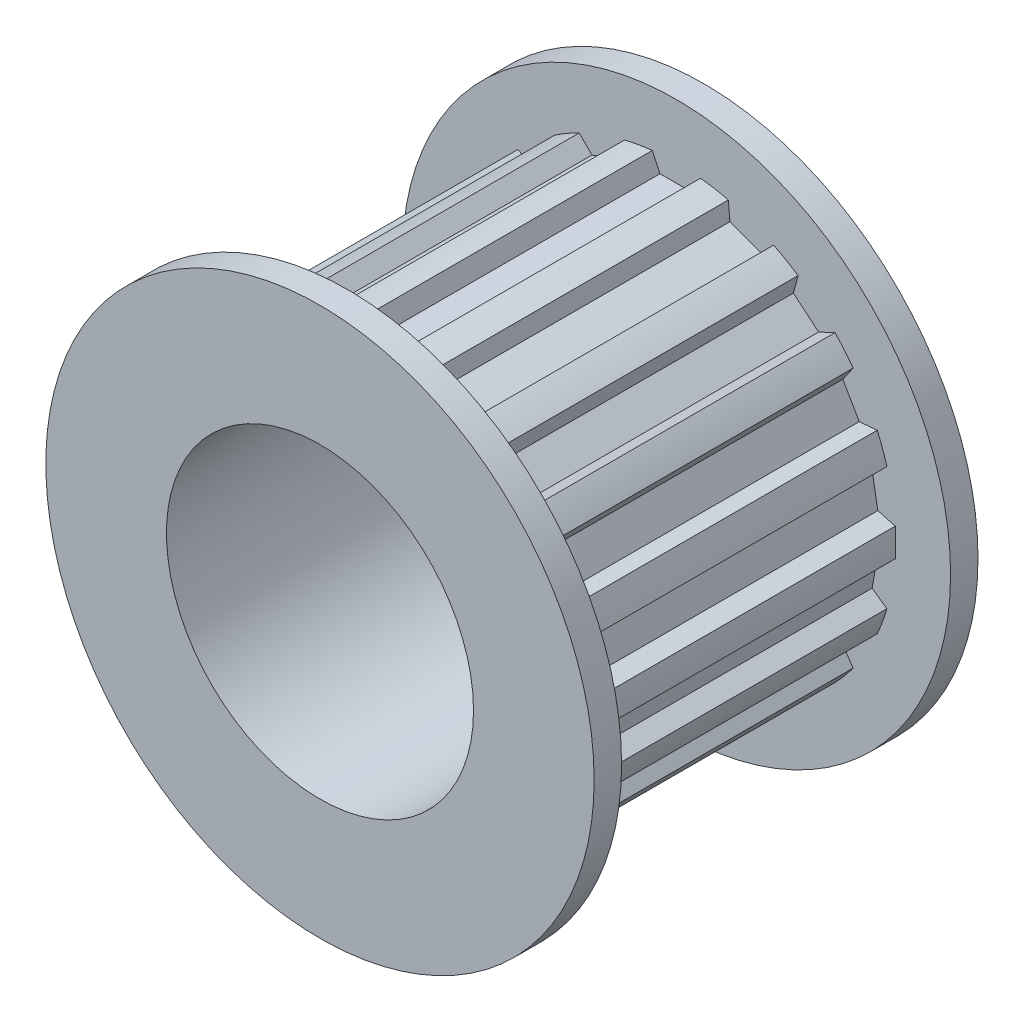
SolidWorks part; units mm, degrees
ref_plane "Plan de face" through (0, 0, 0) normal (0, 0, 1) x (1, 0, 0)
ref_plane "Plan de dessus" through (0, 0, 0) normal (0, 1, 0) x (1, 0, 0)
ref_plane "Plan de droite" through (0, 0, 0) normal (1, 0, 0) x (0, 0, -1)
sketch "Esquisse1" plane through (0, 0, 0) normal (0, 0, 1) x (1, 0, 0)
  circle A0 centre (0, 0) radius 8
  circle A1 centre (0, 0) radius 5.6
extrude "Extrusion1" add sketch "Esquisse1" along normal blind 12
sketch "Esquisse2" plane through (0, 0, 12) normal (0, 0, 1) x (1, 0, 0)
  line L0 (0, 0) -> (0, 16.2125) construction
  line L1 (-0.6, 7.3535) -> (0.6, 7.3535)
  line L2 (0.6, 7.3535) -> (1.0023, 8.2162)
  line L3 (1.0023, 8.2162) -> (-1.0023, 8.2162)
  line L4 (-1.0023, 8.2162) -> (-0.6, 7.3535)
  dimension "D1" = 25
  dimension "D2" = 50
  dimension "D3" = 0.6
  dimension "D4" = 0.6
extrude "Extrusion2" cut sketch "Esquisse2" against normal through all
pattern_circular "Répétition circulaire1" count 18 over 360 about axis through (0, 0, 0) along (0, 0, 1) of "Extrusion2"
sketch "Esquisse3" plane through (0, 0, 12) normal (0, 0, 1) x (1, 0, 0)
  circle A0 centre (0, 0) radius 10
  circle A1 centre (0, 0) radius 5.6
extrude "Extrusion3" add sketch "Esquisse3" along normal blind 1
pattern_linear "Répétition linéaire1" count 2 spacing 13 along (0, 0, -1) of "Extrusion3"
